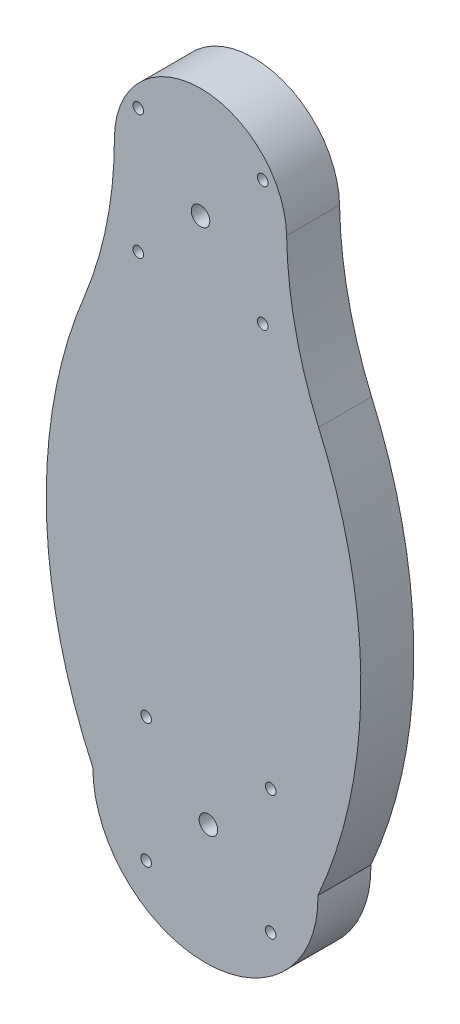
SolidWorks part; units mm, degrees
material "PVC 0.007 Plasticized"
ref_plane "Front Plane" through (0, 0, 0) normal (0, 0, 1) x (1, 0, 0)
ref_plane "Top Plane" through (0, 0, 0) normal (0, 1, 0) x (1, 0, 0)
ref_plane "Right Plane" through (0, 0, 0) normal (1, 0, 0) x (0, 0, -1)
sketch "Sketch1" plane through (0, 0, 0) normal (0, 0, 1) x (1, 0, 0)
  line L0 (-1.8442, 165.0306) -> (0, -44.9694) construction
  arc A0 (-42.5, -44.9694) -> (42.4934, -44.223) centre (0, -44.9694) ccw
  arc A1 (30.6508, 165.6013) -> (-34.3442, 165.0306) centre (-1.8442, 165.0306) ccw
  arc A2 (-34.3442, 165.0306) -> (-45.4471, 108.174) centre (-185.4726, 165.0306) cw
  arc A3 (-45.4471, 108.174) -> (-42.5, -44.9694) centre (130.369, 34.9574) ccw
  arc A4 (42.7506, 108.9486) -> (42.4934, -44.223) centre (-131.7526, 32.6555) cw
  arc A5 (30.6508, 165.6013) -> (42.7506, 108.9486) centre (181.756, 168.2555) ccw
  dimension "D1" = 85
  dimension "D2" = 65
  dimension "D3" = 210
extrude "Boss-Extrude1" add sketch "Sketch1" along normal blind 20
sketch "Sketch2" plane through (0, 0, 20) normal (0, 0, 1) x (1, 0, 0)
  circle A0 centre (-1.8442, 155.7989) radius 3.5
  circle A1 centre (21.6558, 179.2989) radius 2
  circle A2 centre (-25.3442, 179.2989) radius 2
  circle A3 centre (21.6558, 132.2989) radius 2
  circle A4 centre (-25.3442, 132.2989) radius 2
  dimension "D1" = 7
  dimension "D2" = 4
  dimension "D3" = 4
  dimension "D4" = 4
  dimension "D5" = 4
  dimension "D6" = 47
  dimension "D7" = 47
  dimension "D8" = 23.5
  dimension "D9" = 23.5
extrude "Cut-Extrude6" cut sketch "Sketch2" against normal through all
sketch "Sketch4" plane through (0, 0, 20) normal (0, 0, 1) x (1, 0, 0)
  circle A0 centre (1.1326, -41.7473) radius 3.5
  circle A1 centre (24.6326, -18.2473) radius 2
  circle A2 centre (-22.3674, -18.2473) radius 2
  circle A3 centre (24.6326, -65.2473) radius 2
  circle A4 centre (-22.3674, -65.2473) radius 2
  dimension "D1" = 7
  dimension "D2" = 4
  dimension "D3" = 4
  dimension "D4" = 4
  dimension "D5" = 4
  dimension "D6" = 47
  dimension "D7" = 47
  dimension "D8" = 23.5
  dimension "D9" = 23.5
extrude "Cut-Extrude8" cut sketch "Sketch4" against normal through all
